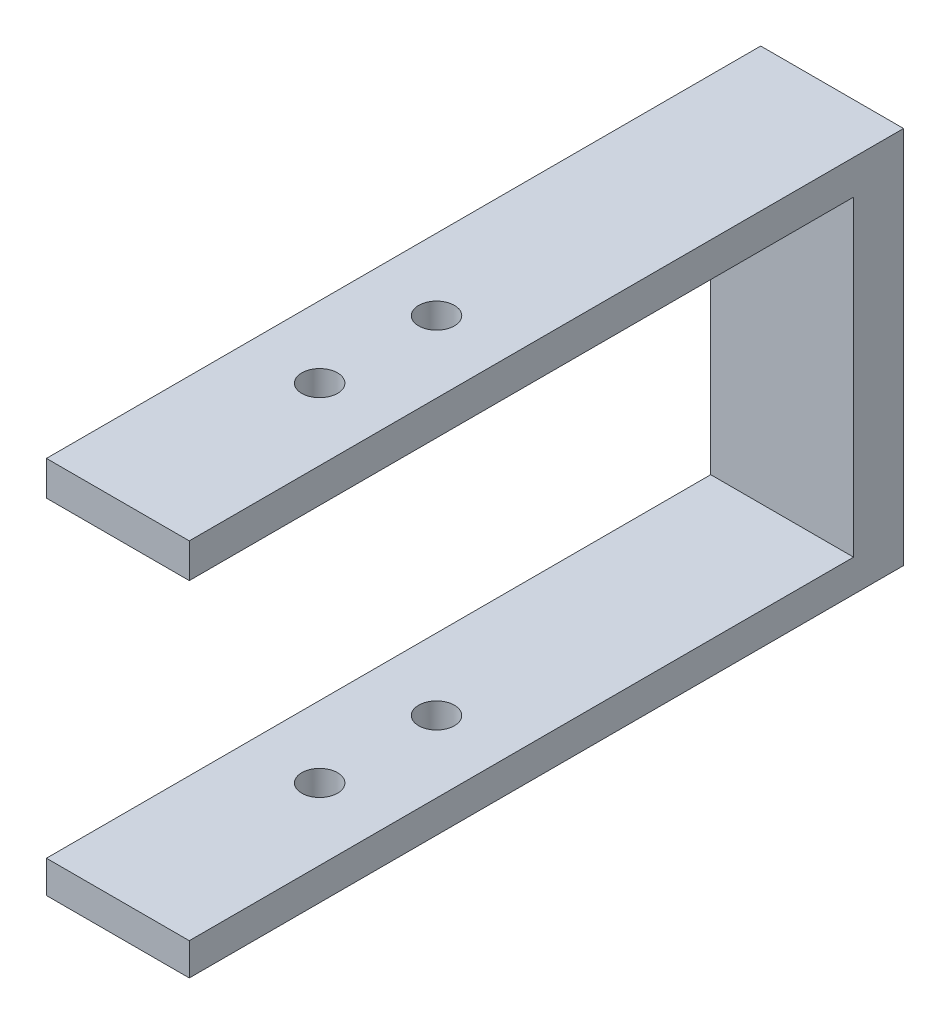
SolidWorks part; units mm, degrees
ref_plane "Front Plane" through (0, 0, 0) normal (0, 0, 1) x (1, 0, 0)
ref_plane "Top Plane" through (0, 0, 0) normal (0, 1, 0) x (1, 0, 0)
ref_plane "Right Plane" through (0, 0, 0) normal (1, 0, 0) x (0, 0, -1)
sketch "Sketch1" plane through (0, 0, 0) normal (0, 1, 0) x (1, 0, 0)
  line L1 (-10, 50) -> (10, 50)
  line L2 (-10, 50) -> (-10, -50)
  line L3 (-10, -50) -> (10, -50)
  line L4 (10, 50) -> (10, -50)
  line L5 (-10, 50) -> (10, -50) construction
  line L6 (-10, -50) -> (10, 50) construction
  point P0 (0, 0)
extrude "Boss-Extrude1" add sketch "Sketch1" along normal blind 53
sketch "Sketch2" plane through (0, 0, 50) normal (0, 0, 1) x (1, 0, 0)
  line L0 (10, 53) -> (10, 0) construction
  line L1 (10, 4.5241) -> (-10, 4.5241)
  line L2 (10, 4.5241) -> (10, 26.6393)
  line L3 (10, 26.6393) -> (-10, 26.6393)
  line L4 (-10, 4.5241) -> (-10, 26.6393)
  line L5 (-10, 53) -> (-10, 0) construction
extrude "Cut-Extrude1" cut sketch "Sketch2" against normal blind 93
sketch "Sketch4" plane through (0, 0, 50) normal (0, 0, 1) x (1, 0, 0)
  line L0 (-10, 53) -> (-10, 26.6393) construction
  line L1 (10, 26.6393) -> (-10, 26.6393)
  line L2 (10, 26.6393) -> (10, 34.0679)
  line L3 (10, 34.0679) -> (-10, 34.0679)
  line L4 (-10, 26.6393) -> (-10, 34.0679)
extrude "Cut-Extrude3" cut sketch "Sketch4" against normal blind 93
sketch "Sketch5" plane through (0, 0, 50) normal (0, 0, 1) x (1, 0, 0)
  line L0 (-10, 53) -> (-10, 34.0679) construction
  line L1 (10, 34.0679) -> (-10, 34.0679)
  line L2 (10, 34.0679) -> (10, 48.1796)
  line L3 (10, 48.1796) -> (-10, 48.1796)
  line L4 (-10, 34.0679) -> (-10, 48.1796)
extrude "Cut-Extrude4" cut sketch "Sketch5" against normal blind 93
sketch "Sketch6" plane through (0, 53, 0) normal (0, 1, 0) x (1, 0, 0)
  circle A0 centre (0, -5.3856) radius 2.5
extrude "Cut-Extrude5" cut sketch "Sketch6" against normal blind 70
sketch "Sketch8" plane through (0, 53, 0) normal (0, 1, 0) x (1, 0, 0)
  circle A0 centre (0, -21.7488) radius 2.5
  point P2 (0, -21.7488)
extrude "Cut-Extrude7" cut sketch "Sketch8" against normal blind 67
